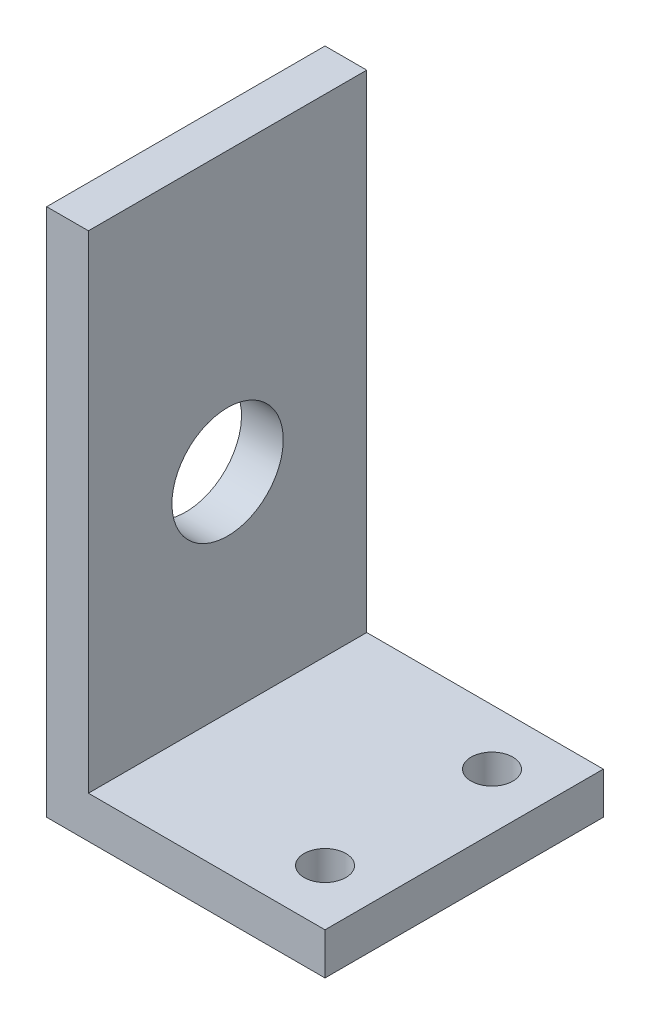
SolidWorks part; units mm, degrees
ref_plane "Front" through (0, 0, 0) normal (0, 0, 1) x (1, 0, 0)
ref_plane "Top" through (0, 0, 0) normal (0, 1, 0) x (1, 0, 0)
ref_plane "Right" through (0, 0, 0) normal (1, 0, 0) x (0, 0, -1)
sketch "草图1" plane through (0, 0, 0) normal (0, 0, 1) x (1, 0, 0)
  line L0 (0, 0) -> (0, 38)
  line L1 (0, 38) -> (3, 38)
  line L2 (3, 38) -> (3, 3)
  line L3 (3, 3) -> (20, 3)
  line L4 (20, 3) -> (20, 0)
  line L5 (20, 0) -> (0, 0)
  dimension "D1" = 38
  dimension "D2" = 3
  dimension "D3" = 35
  dimension "D4" = 17
extrude "凸台-拉伸1" add sketch "草图1" along normal blind 20
sketch "草图2" plane through (0, 3, 0) normal (0, 1, 0) x (1, 0, 0)
  line L0 (16, 0) -> (16, -20) construction
  line L1 (20, 0) -> (3, 0) construction
  line L2 (20, -20) -> (3, -20) construction
  line L3 (20, -20) -> (20, 0) construction
  circle A0 centre (16, -16) radius 1.5
  circle A1 centre (16, -4) radius 1.5
  dimension "D2" = 3
  dimension "D3" = 3
  dimension "D1" = 4
  dimension "D4" = 12
  dimension "D5" = 4
extrude "切除-拉伸1" cut sketch "草图2" against normal through all
sketch "草图3" plane through (3, 0, 0) normal (1, 0, 0) x (0, 0, -1)
  circle A0 centre (-10, 18) radius 4
  dimension "D1" = 8
extrude "切除-拉伸2" cut sketch "草图3" against normal through all
